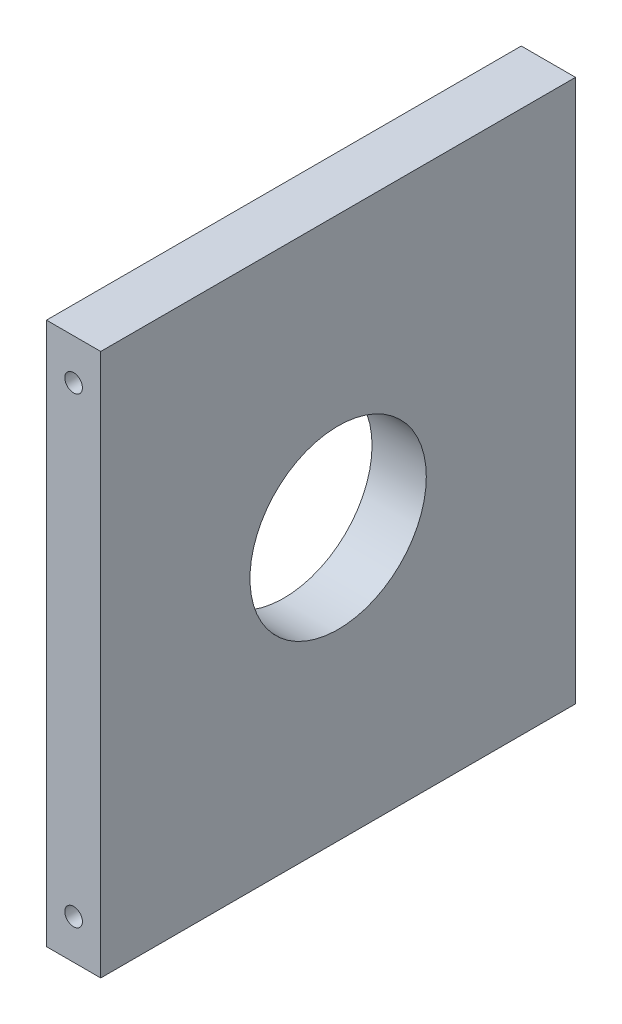
SolidWorks part; units mm, degrees
ref_plane "前视基准面" through (0, 0, 0) normal (0, 0, 1) x (1, 0, 0)
ref_plane "上视基准面" through (0, 0, 0) normal (0, 1, 0) x (1, 0, 0)
ref_plane "右视基准面" through (0, 0, 0) normal (1, 0, 0) x (0, 0, -1)
sketch "草图1" plane through (0, 0, 0) normal (1, 0, 0) x (0, 0, -1)
  line L1 (-35, 40) -> (35, 40)
  line L2 (-35, 40) -> (-35, -40)
  line L3 (-35, -40) -> (35, -40)
  line L4 (35, 40) -> (35, -40)
  line L5 (-35, 40) -> (35, -40) construction
  line L6 (-35, -40) -> (35, 40) construction
  point P0 (0, 0)
  dimension "D1" = 80
  dimension "D2" = 70
extrude "凸台-拉伸1" add sketch "草图1" along normal blind 8
sketch "草图4" plane through (8, 0, 0) normal (1, 0, 0) x (0, 0, -1)
  circle A0 centre (0, 0) radius 13
  dimension "D1" = 26
extrude "切除-拉伸2" cut sketch "草图4" against normal blind 8
sketch "草图5" plane through (0, 0, 35) normal (0, 0, 1) x (1, 0, 0)
  circle A0 centre (4, 34) radius 1.3
  circle A1 centre (4, -34.1568) radius 1.3
  dimension "D1" = 2.6
  dimension "D2" = 2.6
extrude "切除-拉伸3" cut sketch "草图5" against normal blind 10
mirror "镜向1" about plane through (0, 0, 0) normal (0, 0, 1) of "切除-拉伸3"
